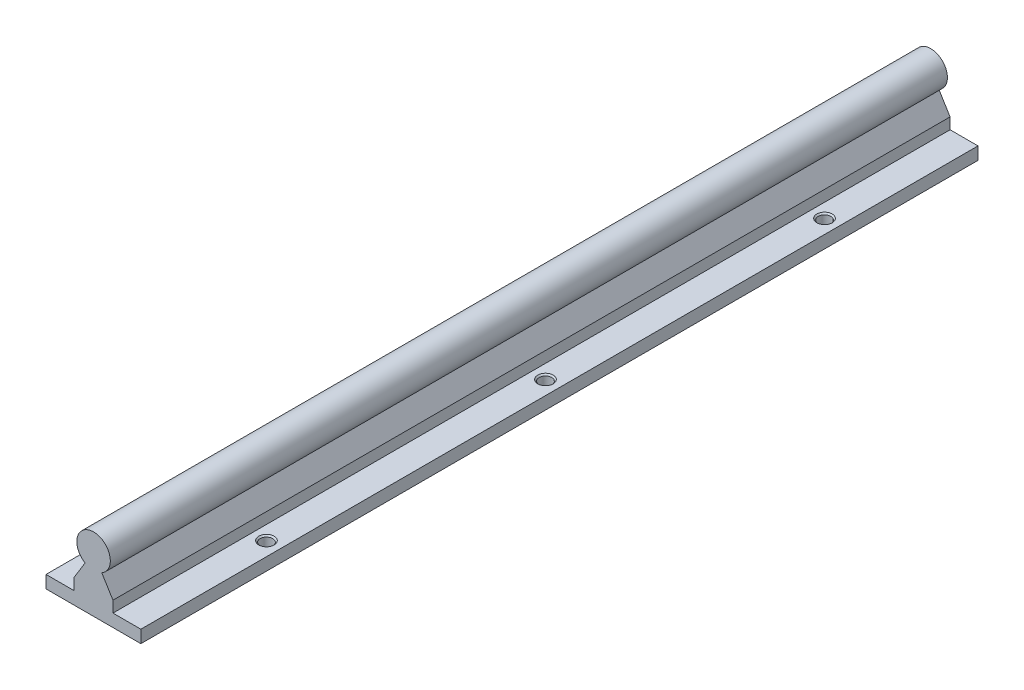
SolidWorks part; units mm, degrees
ref_plane "Plan de face" through (0, 0, 0) normal (0, 0, 1) x (1, 0, 0)
ref_plane "Plan de dessus" through (0, 0, 0) normal (0, 1, 0) x (1, 0, 0)
ref_plane "Plan de droite" through (0, 0, 0) normal (1, 0, 0) x (0, 0, -1)
sketch "Esquisse1" plane through (0, 0, 0) normal (0, 0, 1) x (1, 0, 0)
  line L0 (-38.8855, -19.8216) -> (-4.8855, -19.8216)
  line L1 (-4.8855, -19.8216) -> (-4.8855, -15.3216)
  line L2 (-4.8855, -15.3216) -> (-14.8855, -15.3216)
  line L3 (-14.8855, -15.3216) -> (-14.8855, -11.3216)
  line L4 (-14.8855, -11.3216) -> (-18.8855, -4.8216)
  line L7 (-24.8855, -4.769) -> (-28.8855, -11.3216)
  line L8 (-28.8855, -11.3216) -> (-28.8855, -15.3216)
  line L9 (-28.8855, -15.3216) -> (-38.8855, -15.3216)
  line L10 (-38.8855, -15.3216) -> (-38.8855, -19.8216)
  arc A0 (-18.8855, -4.8216) -> (-24.8855, -4.769) centre (-21.8399, 0.4006) ccw
  dimension "D11" = 12
  dimension "D1" = 4.5
  dimension "D2" = 4
  dimension "D3" = 34
  dimension "D4" = 14
  dimension "D5" = 10
  dimension "D6" = 6
  dimension "D9" = 15
  dimension "D10" = 4
extrude "Extrusion1" add sketch "Esquisse1" along normal blind 300
hole_wizard "Fraisage pour vis à tête fraisée M41" positions "Esquisse3D1" profile "Esquisse2" countersink size "M4" standard "Ansi Métrique" end condition through all
sketch3d "Esquisse3D1"
  line L0 (-28.8855, -15.3216, 0) -> (-38.8855, -15.3216, 0) construction
  line L1 (-4.8855, -15.3216, 0) -> (-14.8855, -15.3216, 0) construction
  line L2 (-38.8855, -15.3216, 300) -> (-38.8855, -15.3216, 0) construction
  line L3 (-4.8855, -15.3216, 300) -> (-4.8855, -15.3216, 0) construction
  point P0 (-33.8855, -15.3216, 50)
  point P2 (-33.8855, -15.3216, 150)
  point P4 (-33.8855, -15.3216, 250)
  point P10 (-9.8855, -15.3216, 250)
  point P12 (-9.8855, -15.3216, 150)
  point P14 (-9.8855, -15.3216, 50)
  dimension "D1" = 50
  dimension "D2" = 150
  dimension "D3" = 250
  dimension "D4" = 50
  dimension "D5" = 150
  dimension "D6" = 250
  dimension "D7" = 5
  dimension "D8" = 5
sketch "Esquisse2" plane through (-33.8855, -15.3216, 50) normal (1, 0, 0) x (0, 0, 1)
  line L0 (0, 0) -> (0, 4.5)
  line L1 (0, 4.5) -> (2.25, 4.5)
  line L2 (2.25, 4.5) -> (2.25, 0.5)
  line L3 (2.25, 0.5) -> (2.75, 0)
  line L5 (2.75, 0) -> (0, 0)
  line L6 (-2.25, 0.5) -> (-2.75, 0) construction
  line L11 (0, -6.35) -> (0, 107.95) construction
  dimension "Diamètre du perçage jusqu'au prochain" = 4.5
  dimension "Profondeur du perçage jusqu'au prochain" = 4.5
  dimension "Diamètre du fraisage entrant" = 5.5
  dimension "Angle du fraisage entrant" = 90
